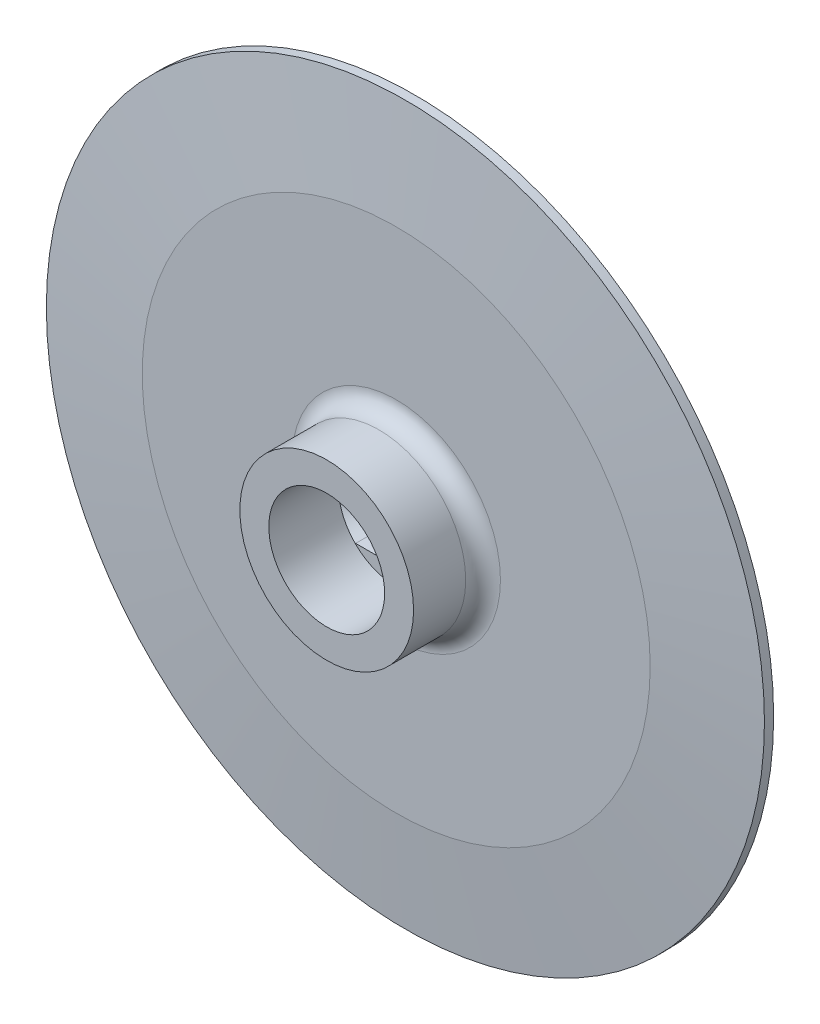
SolidWorks part; units mm, degrees
ref_plane "Front Plane" through (0, 0, 0) normal (0, 0, 1) x (1, 0, 0)
ref_plane "Top Plane" through (0, 0, 0) normal (0, 1, 0) x (1, 0, 0)
ref_plane "Right Plane" through (0, 0, 0) normal (1, 0, 0) x (0, 0, -1)
sketch "Sketch1" plane through (0, 0, 0) normal (0, 0, 1) x (1, 0, 0)
  circle A0 centre (0, 0) radius 15.5
  dimension "D1" = 31
extrude "Boss-Extrude1" add sketch "Sketch1" along normal blind 0.3969
sketch "Sketch2" plane through (0, 0, 0.3969) normal (0, 0, 1) x (1, 0, 0)
  circle A0 centre (0, 0) radius 15.5
  circle A1 centre (0, 0) radius 15.5 construction
extrude "Boss-Extrude2" add sketch "Sketch2" along normal blind 0.3969 draft 85
sketch "Sketch3" plane through (0, 0, 0.7937) normal (0, 0, 1) x (1, 0, 0)
  circle A0 centre (0, 0) radius 3.75
  dimension "D1" = 7.5
extrude "Boss-Extrude3" add sketch "Sketch3" along normal blind 3
fillet "Fillet1" radius 0.75 1 edges at (3.75, 0, 0.7937)
sketch "Sketch4" plane through (0, 0, 0) normal (0, 0, -1) x (-1, 0, 0)
  line L0 (-1.75, 0) -> (1.75, 0) construction
  line L1 (-1.75, 1.75) -> (1.75, 1.75)
  line L2 (-1.75, -1.75) -> (1.75, -1.75)
  arc A0 (-1.75, 1.75) -> (-1.75, -1.75) centre (-1.75, 0) ccw
  arc A1 (1.75, -1.75) -> (1.75, 1.75) centre (1.75, 0) ccw
  point P2 (0, 0)
  dimension "D1" = 3.5
  dimension "D2" = 3.5
extrude "Cut-Extrude1" cut sketch "Sketch4" against normal blind 0.7937
sketch "Sketch5" plane through (0, 0, 3.7938) normal (0, 0, 1) x (1, 0, 0)
  circle A0 centre (0, 0) radius 2.5
  dimension "D1" = 5
extrude "Cut-Extrude2" cut sketch "Sketch5" against normal up to surface (3 mm away) up to face at (0, 0, 0.7937)
